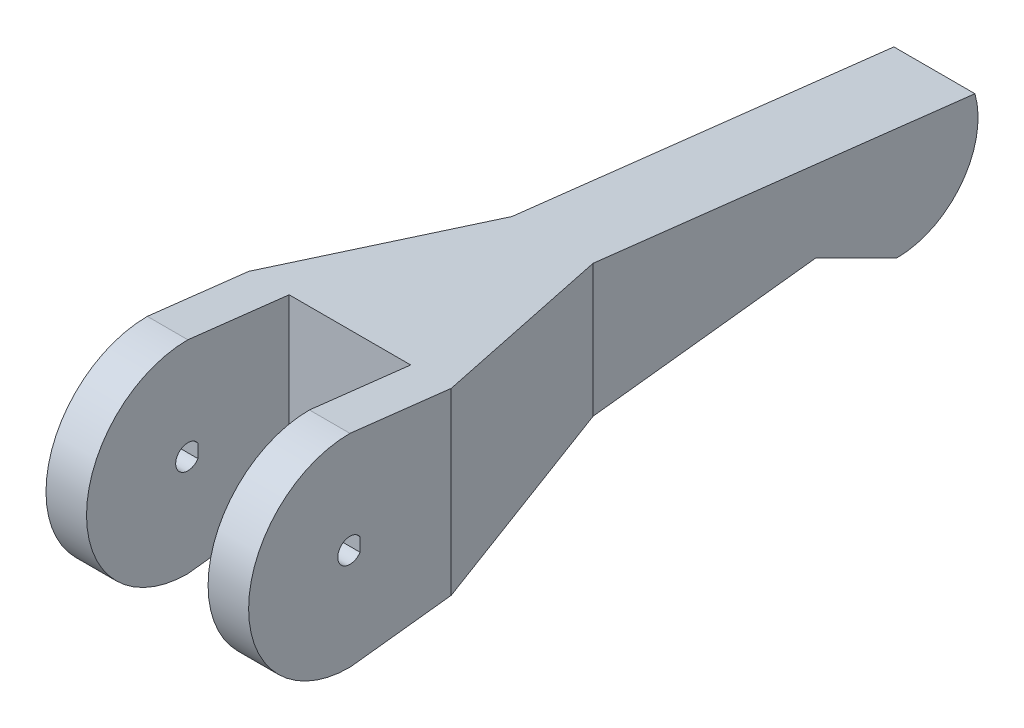
SolidWorks part; units mm, degrees
ref_plane "Front Plane" through (0, 0, 0) normal (0, 0, 1) x (1, 0, 0)
ref_plane "Top Plane" through (0, 0, 0) normal (0, 1, 0) x (1, 0, 0)
ref_plane "Right Plane" through (0, 0, 0) normal (1, 0, 0) x (0, 0, -1)
sketch "Sketch1" plane through (0, 0, 0) normal (1, 0, 0) x (0, 0, -1)
  line L0 (0, 25) -> (130, 10)
  line L1 (130, 10) -> (150, 20)
  line L2 (0, -25) -> (130, -10)
  line L3 (130, -10) -> (150, -20)
  line L4 (0, 0) -> (150, 0) construction
  line L5 (130, 10) -> (130, -10) construction
  arc A0 (0, 25) -> (0, -25) centre (0, 0) ccw
  arc A2 (150, -20) -> (150, 20) centre (150, 0) ccw
  point P11 (130, 0)
  dimension "D1" = 50
  dimension "D4" = 20
  dimension "D2" = 150
  dimension "D3" = 20
  dimension "D5" = 20
extrude "Boss-Extrude1" add sketch "Sketch1" along normal blind 50
sketch "Sketch3" plane through (0, 0, 0) normal (0, 1, 0) x (1, 0, 0)
  line L0 (15, 170) -> (15, 75)
  line L1 (50, 170) -> (0, 170) construction
  line L2 (15, 75) -> (0, 25)
  line L3 (0, 130) -> (0, 0) construction
  line L4 (35, 170) -> (35, 75)
  line L5 (35, 75) -> (50, 25)
  line L6 (50, 130) -> (50, 0) construction
  line L7 (15, 75) -> (35, 75) construction
  line L8 (0, 25) -> (50, 25) construction
  line L9 (0, -25) -> (50, -25) construction
  line L10 (0, 25) -> (-45.1493, 25)
  line L11 (-45.1493, 25) -> (-45.1493, 231.9888)
  line L12 (-45.1493, 231.9888) -> (97.6615, 231.9888)
  line L13 (97.6615, 231.9888) -> (97.6615, 25)
  line L14 (97.6615, 25) -> (50, 25)
  line L15 (15, 170) -> (35, 170)
  point P9 (25, 75)
  point P13 (25, 25)
  dimension "D1" = 20
  dimension "D2" = 50
  dimension "D3" = 50
extrude "Cut-Extrude1" cut sketch "Sketch3" against normal through all both and the other way through all
sketch "Sketch5" plane through (0, 0, 0) normal (0, 1, 0) x (1, 0, 0)
  line L0 (0, -25) -> (50, -25) construction
  line L1 (40, -25) -> (10, -25)
  line L2 (40, -25) -> (40, 25)
  line L3 (40, 25) -> (10, 25)
  line L4 (10, -25) -> (10, 25)
  line L7 (0, 0) -> (50, 0) construction
  point P6 (25, 25)
  point P7 (25, 0)
  dimension "D1" = 50
  dimension "D2" = 30
extrude "Cut-Extrude5" cut sketch "Sketch5" against normal through all both and the other way through all
sketch "Sketch6" plane through (15, 0, 0) normal (-1, 0, 0) x (0, 0, 1)
  line L0 (-130, 10) -> (-189.136, 3.1766)
  line L1 (-189.136, 3.1766) -> (-191.5542, 31.6878)
  line L2 (-191.5542, 31.6878) -> (-130.1719, 25.2467)
  line L3 (-130.1719, 25.2467) -> (-130, 10)
  line L4 (-130, 10) -> (-75, 16.3462) construction
  point P4 (-125.137, 10)
  point P6 (-130.6905, 10.3452)
  point P7 (-130, 25.2476)
extrude "Cut-Extrude6" cut sketch "Sketch6" against normal through all both and the other way through all
sketch "Sketch7" plane through (0, 0, 0) normal (-1, 0, 0) x (0, 0, 1)
  line L0 (-2.5, 1.6583) -> (-2.5, -1.6583)
  line L1 (-25, 22.1154) -> (-25, -22.1154) construction
  line L2 (3, 5.7581) -> (3, -4.813) construction
  arc A0 (-2.5, -1.6583) -> (-2.5, 1.6583) centre (0, 0) ccw
  dimension "D1" = 6
  dimension "D2" = 5.5
extrude "Cut-Extrude7" cut sketch "Sketch7" against normal through all both and the other way through all
